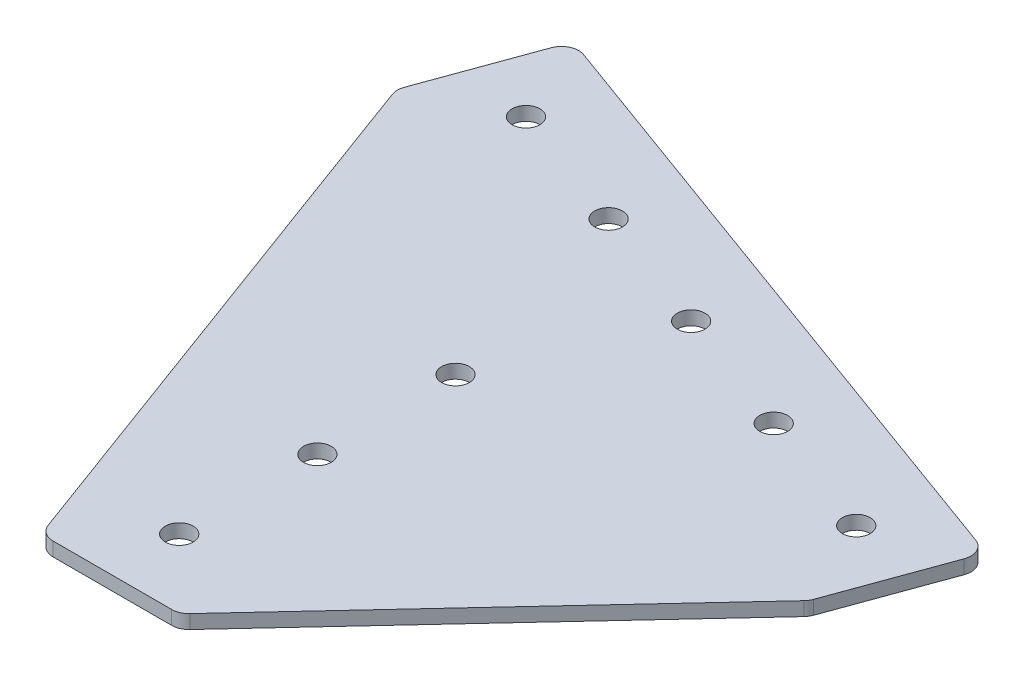
SolidWorks part; units mm, degrees
material "5052-H32"
ref_plane "Front Plane" through (0, 0, 0) normal (0, 0, 1) x (1, 0, 0)
ref_plane "Top Plane" through (0, 0, 0) normal (0, 1, 0) x (1, 0, 0)
ref_plane "Right Plane" through (0, 0, 0) normal (1, 0, 0) x (0, 0, -1)
sketch "Sketch1" plane through (0, 0, 0) normal (0, 1, 0) x (1, 0, 0)
  line L0 (0, 0) -> (-38.152, 103.4517)
  line L1 (-38.152, 103.4517) -> (-29.4647, 127.3199)
  line L2 (-29.4647, 127.3199) -> (89.8762, 83.8833)
  line L3 (89.8762, 83.8833) -> (81.1889, 60.0152)
  line L4 (81.1889, 60.0152) -> (25.4, 0)
  line L5 (25.4, 0) -> (0, 0)
  line L6 (-38.152, 103.4517) -> (81.1889, 60.0152) construction
  line L7 (0, 0) -> (25.4, 0) construction
  line L8 (0, 0) -> (0, 76.2) construction
  line L9 (0, 76.2) -> (25.4, 76.2) construction
  line L10 (25.4, 0) -> (25.4, 76.2) construction
  line L11 (0, 0) -> (25.4, 76.2) construction
  line L12 (0, 76.2) -> (25.4, 0) construction
  line L13 (-33.8084, 115.3858) -> (85.5326, 71.9493) construction
  line L14 (12.7, 76.2) -> (12.7, 0) construction
  point P10 (12.7, 38.1)
  point P14 (12.7, 63.5)
  point P15 (12.7, 12.7)
  point P16 (-21.8743, 111.0422)
  point P17 (1.9939, 102.3548)
  point P18 (25.8621, 93.6675)
  point P19 (49.7303, 84.9802)
  point P20 (73.5985, 76.2929)
  dimension "D1" = 25.4
  dimension "D2" = 20
  dimension "D3" = 76.2
  dimension "D4" = 17.4675
  dimension "D5" = 12.7
  dimension "D6" = 25.4
  dimension "D7" = 25.4
  dimension "D8" = 25.4
  dimension "D9" = 25.4
  dimension "D10" = 25.4
  dimension "D11" = 12.7
  dimension "D12" = 12.7
  dimension "D13" = 38.152
extrude "Boss-Extrude1" add sketch "Sketch1" along normal blind 2.54
hole_wizard "#7 (0.201) Diameter Hole1" positions "Sketch2" profile "Sketch3" hole size "#7" standard "ANSI Inch" end condition through all
sketch "Sketch2" plane through (0, 0, 0) normal (0, -1, 0) x (-1, 0, 0)
  line L0 (33.8084, 115.3858) -> (-85.5326, 71.9493) construction
  point P0 (-73.5985, 76.2929)
  point P3 (-49.7303, 84.9802)
  point P6 (-25.8621, 93.6675)
  point P10 (-1.9939, 102.3548)
  point P13 (21.8743, 111.0422)
  point P16 (-12.7, 63.5)
  point P19 (-12.7, 38.1)
  point P22 (-12.7, 12.7)
sketch "Sketch3" plane through (73.5985, 0, -76.2929) normal (1, 0, 0) x (0, 0, -1)
  line L0 (0, 0) -> (0, 2.54)
  line L1 (0, 2.54) -> (2.5527, 2.54)
  line L2 (2.5527, 2.54) -> (2.5527, 0)
  line L5 (2.5527, 0) -> (0, 0)
  line L11 (0, -6.35) -> (0, 107.95) construction
  dimension "Thru Hole Dia." = 5.1054
  dimension "Thru Hole Depth" = 2.54
fillet "Fillet1" radius 3.175 6 edges at (-38.152, 1.27, -103.4517) (-29.4647, 1.27, -127.3199) (0, 1.27, 0) (25.4, 1.27, 0) (81.1889, 1.27, -60.0152) (89.8762, 1.27, -83.8833)
